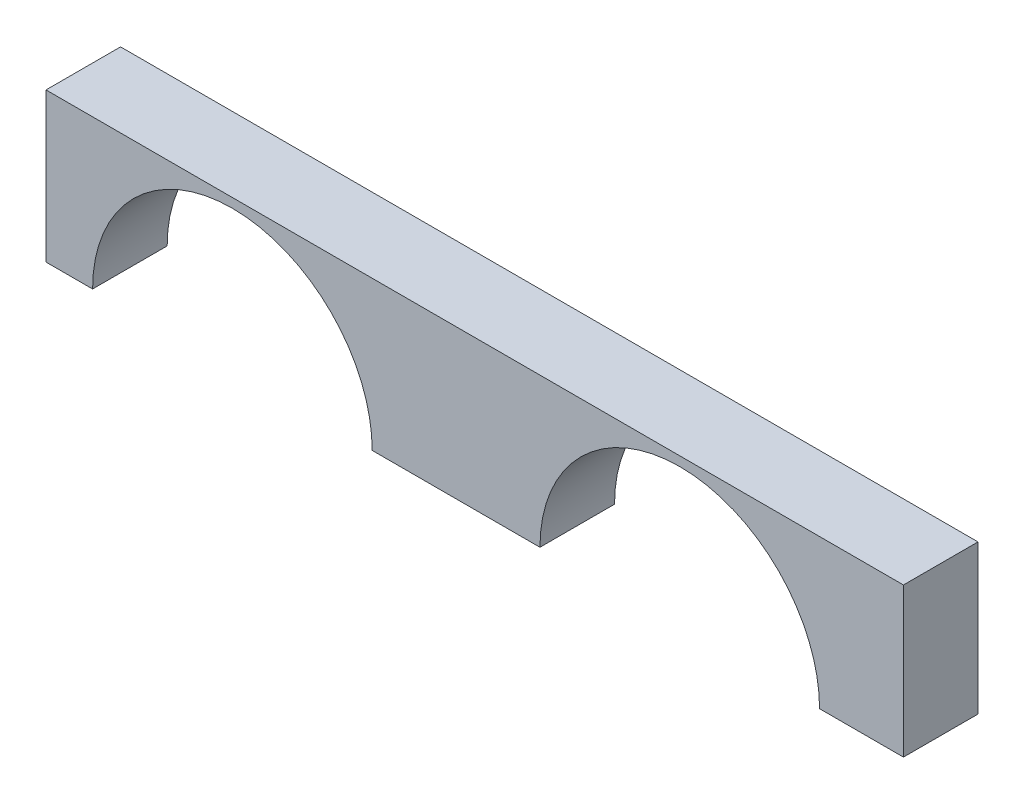
SolidWorks part; units mm, degrees
ref_plane "Front Plane" through (0, 0, 0) normal (0, 0, 1) x (1, 0, 0)
ref_plane "Top Plane" through (0, 0, 0) normal (0, 1, 0) x (1, 0, 0)
ref_plane "Right Plane" through (0, 0, 0) normal (1, 0, 0) x (0, 0, -1)
sketch "Sketch1" plane through (0, 0, 0) normal (0, 0, 1) x (1, 0, 0)
  line L1 (0, 0) -> (230, 0)
  line L2 (0, 0) -> (0, 40)
  line L3 (0, 40) -> (230, 40)
  line L4 (230, 0) -> (230, 40)
  dimension "D1" = 230
  dimension "D2" = 40
extrude "Boss-Extrude1" add sketch "Sketch1" along normal blind 20
sketch "Sketch2" plane through (0, 0, 20) normal (0, 0, 1) x (1, 0, 0)
  line L0 (0, 0) -> (230, 0) construction
  line L1 (0, 40) -> (0, 0) construction
  line L2 (230, 0) -> (230, 40) construction
  circle A0 centre (50, 0) radius 37.5
  circle A1 centre (170, 0) radius 37.5
  dimension "D1" = 75
  dimension "D2" = 75
  dimension "D3" = 50
  dimension "D4" = 60
extrude "Cut-Extrude1" cut sketch "Sketch2" against normal through all
